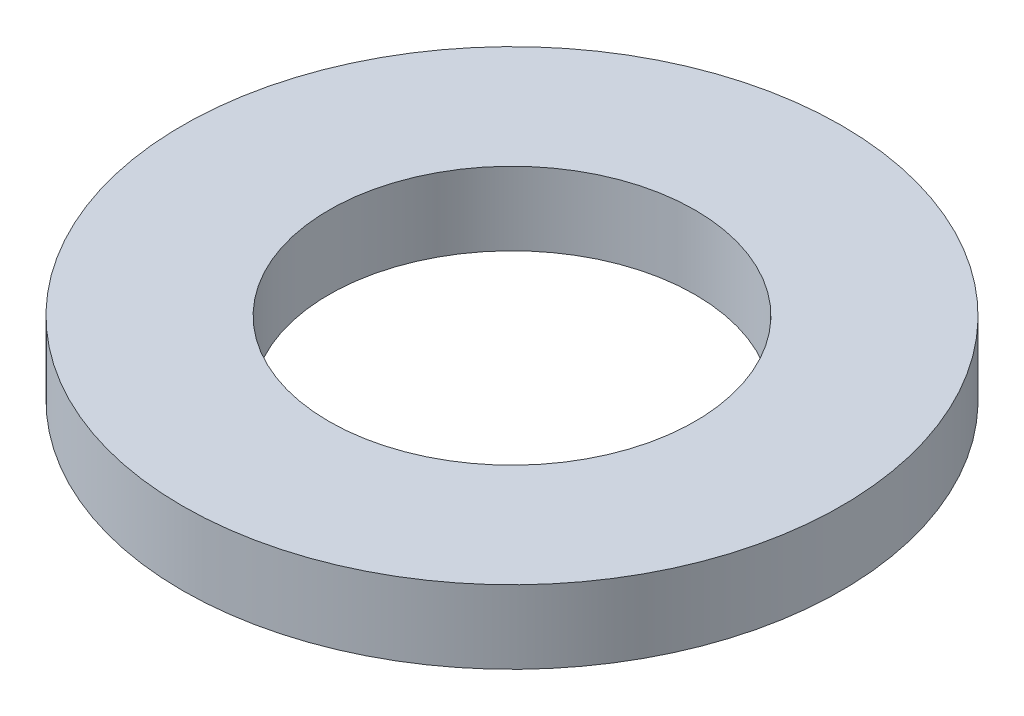
SolidWorks part; units mm, degrees
material "铜"
ref_plane "前视基准面" through (0, 0, 0) normal (0, 0, 1) x (1, 0, 0)
ref_plane "上视基准面" through (0, 0, 0) normal (0, 1, 0) x (1, 0, 0)
ref_plane "右视基准面" through (0, 0, 0) normal (1, 0, 0) x (0, 0, -1)
sketch "草图1" plane through (0, 0, 0) normal (0, 1, 0) x (1, 0, 0)
  circle A0 centre (0, 0) radius 2.5
  circle A1 centre (0, 0) radius 4.5
  dimension "D1" = 9
  dimension "D2" = 5
extrude "凸台-拉伸1" add sketch "草图1" along normal blind 1
move or copy body "实体-移动/复制1" [suppressed] bodies to move or copy 106
